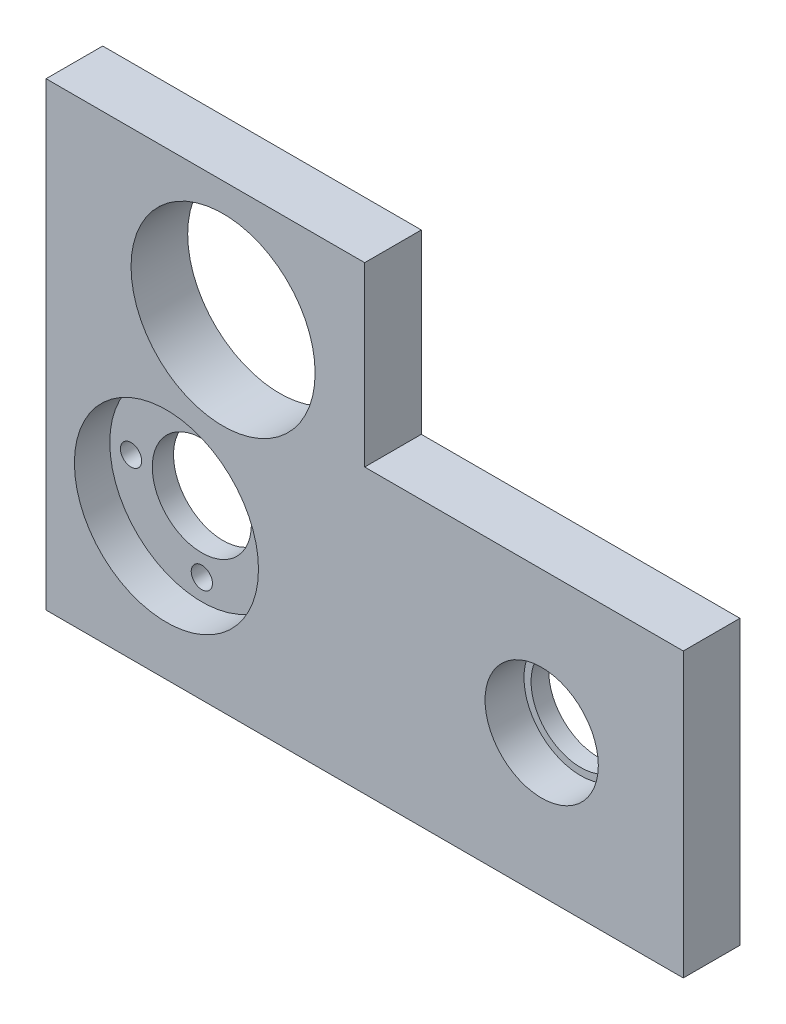
SolidWorks part; units mm, degrees
ref_plane "Front" through (0, 0, 0) normal (0, 0, 1) x (1, 0, 0)
ref_plane "Top" through (0, 0, 0) normal (0, 1, 0) x (1, 0, 0)
ref_plane "Right" through (0, 0, 0) normal (1, 0, 0) x (0, 0, -1)
sketch "Esquisse1" plane through (0, 0, 0) normal (0, 0, 1) x (1, 0, 0)
  line L1 (0, 0) -> (90, 0)
  line L2 (0, 0) -> (0, 65)
  line L3 (0, 65) -> (90, 65)
  line L4 (90, 0) -> (90, 65)
  circle A0 centre (70, 20) radius 7
  circle A1 centre (17, 20) radius 13
  circle A2 centre (25, 48) radius 13
  dimension "D3" = 14
  dimension "D4" = 20
  dimension "D6" = 53
  dimension "D8" = 26
  dimension "D9" = 26
  dimension "D1" = 90
  dimension "D2" = 65
  dimension "D5" = 70
  dimension "D7" = 20
  dimension "D10" = 53
  dimension "D11" = 48
extrude "Boss.-Extru.1" add sketch "Esquisse1" along normal blind 8
sketch "Esquisse2" plane through (0, 0, 0) normal (0, 0, -1) x (-1, 0, 0)
  circle A0 centre (-17, 20) radius 13
  circle A1 centre (-17, 20) radius 13 construction
extrude "Boss.-Extru.2" add sketch "Esquisse2" against normal blind 3
sketch "Esquisse3" plane through (0, 0, 3) normal (0, 0, 1) x (1, 0, 0)
  line L0 (27, 20) -> (17, 20) construction
  circle A0 centre (17, 20) radius 7
  circle A1 centre (27, 20) radius 1.5
  circle A2 centre (17, 10) radius 1.5
  circle A3 centre (7, 20) radius 1.5
  circle A4 centre (17, 30) radius 1.5
  point P13 (17, 20)
  dimension "D1" = 14
  dimension "D2" = 3
  dimension "D3" = 10
  dimension "D4" = 4
extrude "Enlèv. mat.-Extru.1" cut sketch "Esquisse3" against normal through all
sketch "Esquisse4" plane through (0, 0, 8) normal (0, 0, 1) x (1, 0, 0)
  circle A0 centre (70, 20) radius 8
  dimension "D1" = 16
extrude "Enlèv. mat.-Extru.2" cut sketch "Esquisse4" against normal blind 5.5
sketch "Esquisse5" plane through (0, 0, 8) normal (0, 0, 1) x (1, 0, 0)
  line L0 (90, 65) -> (0, 65) construction
  line L1 (45, 65) -> (90, 65)
  line L2 (45, 65) -> (45, 40)
  line L3 (45, 40) -> (90, 40)
  line L4 (90, 65) -> (90, 40)
  line L5 (90, 0) -> (90, 65) construction
  dimension "D1" = 25
  dimension "D2" = 45
extrude "Enlèv. mat.-Extru.3" cut sketch "Esquisse5" against normal through all
